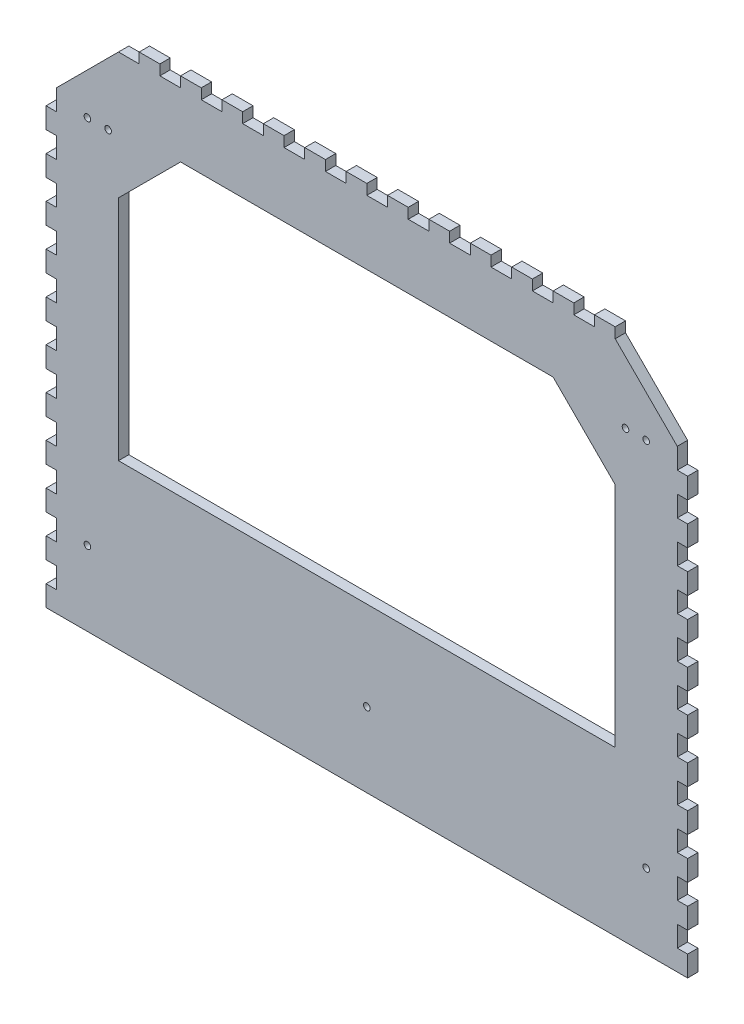
SolidWorks part; units mm, degrees
material "Buche"
ref_plane "Ebene vorne" through (0, 0, 0) normal (0, 0, 1) x (1, 0, 0)
ref_plane "Ebene oben" through (0, 0, 0) normal (0, 1, 0) x (1, 0, 0)
ref_plane "Ebene rechts" through (0, 0, 0) normal (1, 0, 0) x (0, 0, -1)
sketch "Skizze1" plane through (0, 0, 0) normal (0, 0, 1) x (1, 0, 0)
  line L0 (5, 10) -> (5, 20)
  line L1 (5, 0) -> (305, 0)
  line L2 (305, 10) -> (305, 20)
  line L3 (55, 250) -> (65, 250)
  line L4 (5, 220) -> (35, 250)
  line L5 (305, 220) -> (275, 250)
  line L6 (275, 188.9712) -> (245, 218.9712)
  line L7 (35, 78.9712) -> (275, 78.9712)
  line L8 (35, 78.9712) -> (35, 188.9712)
  line L9 (65, 218.9712) -> (245, 218.9712)
  line L10 (275, 78.9712) -> (275, 188.9712)
  line L11 (35, 188.9712) -> (65, 218.9712)
  line L12 (35, 250) -> (45, 250)
  line L13 (305, 0) -> (310, 0)
  line L14 (310, 0) -> (310, 10)
  line L15 (310, 10) -> (305, 10)
  line L16 (305, 30) -> (305, 40)
  line L17 (305, 20) -> (310, 20)
  line L18 (310, 20) -> (310, 30)
  line L19 (310, 30) -> (305, 30)
  line L20 (305, 50) -> (305, 60)
  line L21 (305, 40) -> (310, 40)
  line L22 (310, 40) -> (310, 50)
  line L23 (310, 50) -> (305, 50)
  line L24 (305, 70) -> (305, 80)
  line L25 (305, 60) -> (310, 60)
  line L26 (310, 60) -> (310, 70)
  line L27 (310, 70) -> (305, 70)
  line L28 (305, 90) -> (305, 100)
  line L29 (305, 80) -> (310, 80)
  line L30 (310, 80) -> (310, 90)
  line L31 (310, 90) -> (305, 90)
  line L32 (305, 110) -> (305, 120)
  line L33 (305, 100) -> (310, 100)
  line L34 (310, 100) -> (310, 110)
  line L35 (310, 110) -> (305, 110)
  line L36 (305, 130) -> (305, 140)
  line L37 (305, 120) -> (310, 120)
  line L38 (310, 120) -> (310, 130)
  line L39 (310, 130) -> (305, 130)
  line L40 (305, 150) -> (305, 160)
  line L41 (305, 140) -> (310, 140)
  line L42 (310, 140) -> (310, 150)
  line L43 (310, 150) -> (305, 150)
  line L44 (305, 170) -> (305, 180)
  line L45 (305, 160) -> (310, 160)
  line L46 (310, 160) -> (310, 170)
  line L47 (310, 170) -> (305, 170)
  line L48 (305, 190) -> (305, 200)
  line L49 (305, 180) -> (310, 180)
  line L50 (310, 180) -> (310, 190)
  line L51 (310, 190) -> (305, 190)
  line L52 (305, 210) -> (305, 220)
  line L53 (305, 200) -> (310, 200)
  line L54 (310, 200) -> (310, 210)
  line L55 (310, 210) -> (305, 210)
  line L56 (5, 0) -> (0, 0)
  line L57 (0, 0) -> (0, 10)
  line L58 (0, 10) -> (5, 10)
  line L59 (5, 30) -> (5, 40)
  line L60 (0, 20) -> (0, 30)
  line L61 (0, 30) -> (5, 30)
  line L62 (5, 50) -> (5, 60)
  line L63 (0, 40) -> (0, 50)
  line L64 (0, 50) -> (5, 50)
  line L65 (5, 70) -> (5, 80)
  line L66 (0, 60) -> (0, 70)
  line L67 (0, 70) -> (5, 70)
  line L68 (5, 90) -> (5, 100)
  line L69 (0, 80) -> (0, 90)
  line L70 (0, 90) -> (5, 90)
  line L71 (5, 110) -> (5, 120)
  line L72 (0, 100) -> (0, 110)
  line L73 (0, 110) -> (5, 110)
  line L74 (5, 130) -> (5, 140)
  line L75 (0, 120) -> (0, 130)
  line L76 (0, 130) -> (5, 130)
  line L77 (5, 150) -> (5, 160)
  line L78 (0, 140) -> (0, 150)
  line L79 (0, 150) -> (5, 150)
  line L80 (5, 170) -> (5, 180)
  line L81 (0, 160) -> (0, 170)
  line L82 (0, 170) -> (5, 170)
  line L83 (5, 190) -> (5, 200)
  line L84 (0, 180) -> (0, 190)
  line L85 (0, 190) -> (5, 190)
  line L86 (5, 210) -> (5, 220)
  line L87 (0, 200) -> (0, 210)
  line L88 (0, 210) -> (5, 210)
  line L89 (0, 20) -> (5, 20)
  line L90 (0, 40) -> (5, 40)
  line L91 (0, 60) -> (5, 60)
  line L92 (0, 80) -> (5, 80)
  line L93 (0, 100) -> (5, 100)
  line L94 (0, 120) -> (5, 120)
  line L95 (0, 140) -> (5, 140)
  line L96 (0, 160) -> (5, 160)
  line L97 (0, 180) -> (5, 180)
  line L98 (0, 200) -> (5, 200)
  line L99 (45, 250) -> (45, 255)
  line L100 (45, 255) -> (55, 255)
  line L101 (55, 255) -> (55, 250)
  line L102 (65, 250) -> (65, 255)
  line L103 (65, 255) -> (75, 255)
  line L104 (75, 255) -> (75, 250)
  line L105 (75, 250) -> (85, 250)
  line L106 (85, 250) -> (85, 255)
  line L107 (85, 255) -> (95, 255)
  line L108 (95, 255) -> (95, 250)
  line L109 (95, 250) -> (105, 250)
  line L110 (105, 250) -> (105, 255)
  line L111 (105, 255) -> (115, 255)
  line L112 (115, 255) -> (115, 250)
  line L113 (115, 250) -> (125, 250)
  line L114 (125, 250) -> (125, 255)
  line L115 (125, 255) -> (135, 255)
  line L116 (135, 255) -> (135, 250)
  line L117 (135, 250) -> (145, 250)
  line L118 (145, 250) -> (145, 255)
  line L119 (145, 255) -> (155, 255)
  line L120 (155, 255) -> (155, 250)
  line L121 (155, 250) -> (165, 250)
  line L122 (165, 250) -> (165, 255)
  line L123 (165, 255) -> (175, 255)
  line L124 (175, 255) -> (175, 250)
  line L125 (175, 250) -> (185, 250)
  line L126 (185, 250) -> (185, 255)
  line L127 (185, 255) -> (195, 255)
  line L128 (195, 255) -> (195, 250)
  line L129 (195, 250) -> (205, 250)
  line L130 (205, 250) -> (205, 255)
  line L131 (205, 255) -> (215, 255)
  line L132 (215, 255) -> (215, 250)
  line L133 (215, 250) -> (225, 250)
  line L134 (225, 250) -> (225, 255)
  line L135 (225, 255) -> (235, 255)
  line L136 (235, 255) -> (235, 250)
  line L137 (235, 250) -> (245, 250)
  line L138 (245, 250) -> (245, 255)
  line L139 (245, 255) -> (255, 255)
  line L140 (255, 255) -> (255, 250)
  line L141 (255, 250) -> (265, 250)
  line L142 (265, 250) -> (265, 255)
  line L143 (265, 255) -> (275, 255)
  line L144 (275, 255) -> (275, 250)
  circle A0 centre (290, 215) radius 1.6
  circle A1 centre (280, 215) radius 1.6
  circle A2 centre (20, 215) radius 1.6
  circle A3 centre (30, 215) radius 1.6
  circle A4 centre (20, 36) radius 1.6
  circle A5 centre (155, 36) radius 1.6
  circle A6 centre (290, 36) radius 1.6
  dimension "D1" = 12
extrude "Aufsatz-Linear austragen1" add sketch "Skizze1" along normal blind 5
